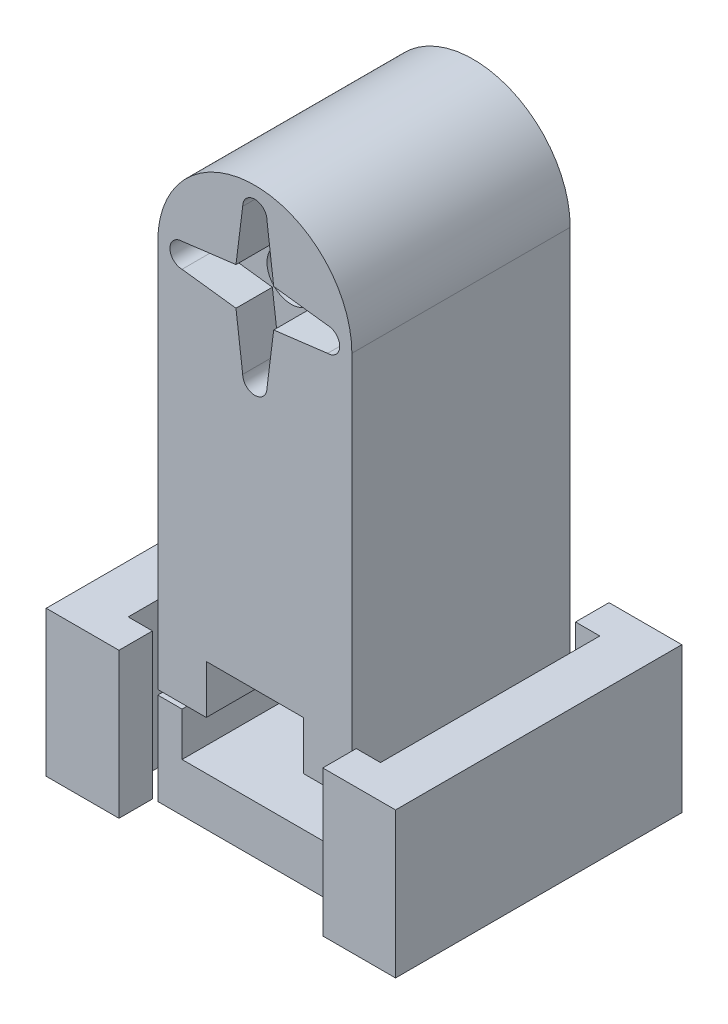
SolidWorks part; units mm, degrees
ref_plane "Alzado" through (0, 0, 0) normal (1, 0, 0) x (0, 1, 0)
ref_plane "Planta" through (0, 0, 0) normal (0, 0, 1) x (0, 1, 0)
ref_plane "Vista lateral" through (0, 0, 0) normal (0, 1, 0) x (-1, 0, 0)
sketch "Croquis1" plane through (0, 0, 0) normal (0, 0, 1) x (0, 1, 0)
  line L4 (0, 20) -> (40, 20)
  line L5 (0, -20) -> (40, -20)
  line L6 (0, 20) -> (-40, 20)
  line L7 (0, -20) -> (-40, -20)
  arc A0 (40, -20) -> (40, 20) centre (40, 0) ccw
  arc A1 (-40, 20) -> (-40, -20) centre (-40, 0) ccw
extrude "Saliente-Extruir1" add sketch "Croquis1" along normal blind 45
sketch "Croquis2" plane through (0, 0, 45) normal (0, 0, 1) x (1, 0, 0)
  line L8 (-15, 42.5) -> (-3.8891, 43.8891)
  line L9 (-3.8891, 43.8891) -> (-2.5, 55)
  line L10 (2.5, 55) -> (3.8891, 43.8891)
  line L11 (15, 42.5) -> (3.8891, 43.8891)
  line L12 (15, 37.5) -> (3.8891, 36.1109)
  line L13 (2.5, 25) -> (3.8891, 36.1109)
  line L14 (-2.5, 25) -> (-3.8891, 36.1109)
  line L15 (-15, 37.5) -> (-3.8891, 36.1109)
  arc A5 (-15, 42.5) -> (-15, 37.5) centre (-15, 40) ccw
  arc A6 (-2.5, 25) -> (2.5, 25) centre (0, 25) ccw
  arc A7 (15, 37.5) -> (15, 42.5) centre (15, 40) ccw
  arc A8 (2.5, 55) -> (-2.5, 55) centre (0, 55) ccw
extrude "Cortar-Extruir1" cut sketch "Croquis2" against normal blind 7.5
sketch "Croquis3" plane through (0, 0, 45) normal (0, 0, 1) x (1, 0, 0)
  circle A0 centre (0, 40) radius 5
extrude "Cortar-Extruir2" cut sketch "Croquis3" against normal blind 57.5
sketch "Croquis4" plane through (0, 0, 45) normal (0, 0, 1) x (1, 0, 0)
  line L1 (20, -40) -> (-21.8685, -40)
  line L2 (20, -40) -> (20, -61.001)
  line L3 (20, -61.001) -> (-21.8685, -61.001)
  line L4 (-21.8685, -40) -> (-21.8685, -61.001)
extrude "Cortar-Extruir3" cut sketch "Croquis4" against normal blind 57.5
sketch "Croquis5" plane through (0, 0, 45) normal (0, 0, 1) x (1, 0, 0)
  line L4 (0, -40) -> (10, -40)
  line L5 (20, -40) -> (-20, -40) construction
  line L6 (0, -40) -> (-10, -40)
  line L7 (-10, -40) -> (-10, 0)
  line L8 (-10, 0) -> (10, 0)
  line L9 (10, 0) -> (10, -40)
  dimension "D1" = 10
  dimension "D2" = 10
  dimension "D3" = 40
extrude "Cortar-Extruir4" cut sketch "Croquis5" against normal blind 40 from offset 2.5 offset against normal yes
sketch "Croquis6" plane through (0, 0, 45) normal (0, 0, 1) x (1, 0, 0)
  line L0 (0, -40) -> (-10, -40)
  line L1 (20, -40) -> (-20, -40) construction
  line L2 (-10, -40) -> (-10, -30)
  line L3 (-10, -30) -> (10, -30)
  line L4 (10, -30) -> (10, -40)
  line L5 (10, -40) -> (0, -40)
extrude "Cortar-Extruir5" cut sketch "Croquis6" against normal blind 45
sketch "Croquis7" plane through (0, 0, 45) normal (0, 0, 1) x (1, 0, 0)
  line L1 (-10, 0) -> (10, 0)
  line L2 (10, 0) -> (10, -10)
  line L3 (10, -10) -> (-10, -10)
  line L4 (-10, -10) -> (-10, 0)
extrude "Cortar-Extruir7" cut sketch "Croquis7" against normal blind 20 from offset 40 offset against normal yes
sketch "Croquis8" plane through (0, 0, 0) normal (0, 0, -1) x (1, 0, 0)
  line L1 (10, 30) -> (20, 30)
  line L2 (10, 30) -> (10, 60)
  line L3 (10, 60) -> (20, 60)
  line L4 (20, 30) -> (20, 60)
  line L5 (20, 60) -> (-20, 60)
  line L6 (20, 60) -> (20, 50)
  line L7 (20, 50) -> (-20, 50)
  line L8 (-20, 60) -> (-20, 50)
  line L9 (-10, 40) -> (-20, 40)
  line L10 (-10, 40) -> (-10, 60)
  line L11 (-10, 60) -> (-20, 60)
  line L12 (-20, 40) -> (-20, 60)
  line M20 (20, 40) -> (10, 40)
  dimension "D1" = 30
  dimension "D2" = 10
  dimension "D3" = 40
extrude "Saliente-Extruir2" add sketch "Croquis8" against normal blind 45 contours L7 L4 L3 L2 | L4 L7 L2 M20 | L10 L7 L2 L5
sketch "Croquis9" plane through (0, 0, 0) normal (0, 0, -1) x (-1, 0, 0)
  line L7 (-10, -40) -> (-15, -40)
  line L8 (-10, -40) -> (-10, -50)
  line L9 (-10, -50) -> (-15, -50)
  line L10 (-15, -40) -> (-15, -50)
  line L11 (10, -50) -> (15, -50)
  line L12 (10, -50) -> (10, -40)
  line L13 (10, -40) -> (15, -40)
  line L14 (15, -50) -> (15, -40)
extrude "Cortar-Extruir8" cut sketch "Croquis9" against normal blind 45
sketch "Croquis10" plane through (0, -60, 0) normal (0, -1, 0) x (1, 0, 0)
  circle A1 centre (0, 12.5) radius 3
extrude "Cortar-Extruir9" cut sketch "Croquis10" against normal blind 20
sketch "Croquis11" plane through (0, 0, 0) normal (0, 0, -1) x (1, 0, 0)
  line L0 (20, 60) -> (20, -40) construction
  line L1 (20, 40) -> (-20, 40)
  line L2 (20, 40) -> (20, 41)
  line L3 (20, 41) -> (-20, 41)
  line L4 (-20, 40) -> (-20, 41)
  line L5 (-20, -40) -> (-20, 60) construction
extrude "Cortar-Extruir12" cut sketch "Croquis11" against normal blind 45
sketch "Croquis12" plane through (0, 0, 45) normal (0, 0, 1) x (1, 0, 0)
  line L1 (-20, -60) -> (-15, -60)
  line L2 (-20, -60) -> (-20, -30)
  line L3 (-20, -30) -> (-15, -30)
  line L4 (-15, -60) -> (-15, -30)
  line L5 (20, -60) -> (15, -60)
  line L6 (20, -60) -> (20, -30)
  line L7 (20, -30) -> (15, -30)
  line L8 (15, -60) -> (15, -30)
  dimension "D1" = 30
  dimension "D2" = 30
extrude "Saliente-Extruir3" add sketch "Croquis12" along normal blind 7
sketch "Croquis13" plane through (20, 0, 0) normal (1, 0, 0) x (0, 1, 0)
  line L0 (-40, 0) -> (40, 0) construction
  line L1 (-60, 52) -> (-30, 52)
  line L2 (-60, 52) -> (-60, 0)
  line L3 (-60, 0) -> (-30, 0)
  line L4 (-30, 52) -> (-30, 0)
extrude "Saliente-Extruir4" add sketch "Croquis13" along normal blind 16
sketch "Croquis14" plane through (-20, 0, 0) normal (-1, 0, 0) x (0, -1, 0)
  line L1 (30, 52) -> (60, 52)
  line L2 (30, 52) -> (30, 0)
  line L3 (30, 0) -> (60, 0)
  line L4 (60, 52) -> (60, 0)
extrude "Saliente-Extruir5" add sketch "Croquis14" along normal blind 16
sketch "Croquis15" plane through (0, 0, 52) normal (0, 0, 1) x (1, 0, 0)
  line L0 (15, -60) -> (36, -60) construction
  line L1 (15, -30) -> (21, -30)
  line L2 (15, -30) -> (15, -60)
  line L3 (15, -60) -> (21, -60)
  line L4 (21, -30) -> (21, -60)
extrude "Cortar-Extruir13" cut sketch "Croquis15" against normal blind 7
sketch "Croquis16" plane through (0, 0, 52) normal (0, 0, 1) x (1, 0, 0)
  line L0 (-36, -60) -> (-15, -60) construction
  line L1 (-15, -30) -> (-21, -30)
  line L2 (-15, -30) -> (-15, -60)
  line L3 (-15, -60) -> (-21, -60)
  line L4 (-21, -30) -> (-21, -60)
extrude "Cortar-Extruir14" cut sketch "Croquis16" against normal blind 7
sketch "Croquis17" plane through (0, 0, 45) normal (0, 0, 1) x (1, 0, 0)
  line L0 (-21, -60) -> (21, -60) construction
  line L1 (20, -30) -> (21, -30)
  line L2 (20, -30) -> (20, -60)
  line L3 (20, -60) -> (21, -60)
  line L4 (21, -30) -> (21, -60)
  line L5 (-21, -30) -> (-20, -30)
  line L6 (-21, -30) -> (-21, -60)
  line L7 (-21, -60) -> (-20, -60)
  line L8 (-20, -30) -> (-20, -60)
extrude "Cortar-Extruir15" cut sketch "Croquis17" against normal blind 45
sketch "Croquis18" plane through (0, 0, 0) normal (0, 0, -1) x (-1, 0, 0)
  line L1 (36, -60) -> (21, -60)
  line L2 (36, -60) -> (36, -30)
  line L3 (36, -30) -> (21, -30)
  line L4 (21, -60) -> (21, -30)
  line L5 (-21, -60) -> (-36, -60)
  line L6 (-21, -60) -> (-21, -30)
  line L7 (-21, -30) -> (-36, -30)
  line L8 (-36, -60) -> (-36, -30)
extrude "Saliente-Extruir6" add sketch "Croquis18" along normal blind 7
sketch "Croquis19" plane through (0, 0, -7) normal (0, 0, -1) x (-1, 0, 0)
  line L0 (36, -30) -> (21, -30) construction
  line L1 (21, -60) -> (26, -60)
  line L2 (21, -60) -> (21, -30)
  line L3 (21, -30) -> (26, -30)
  line L4 (26, -60) -> (26, -30)
  point P17 (-26.757, -60)
  point P18 (-28.8529, -62.9007)
  dimension "D1" = 5
extrude "Cortar-Extruir16" cut sketch "Croquis19" against normal blind 45.2 from offset 6.9 offset against normal yes
sketch "Croquis20" plane through (0, 0, -7) normal (0, 0, -1) x (1, 0, 0)
  line L0 (21, 30) -> (36, 30) construction
  line L1 (21, 60) -> (26, 60)
  line L2 (21, 60) -> (21, 30)
  line L3 (21, 30) -> (26, 30)
  line L4 (26, 60) -> (26, 30)
extrude "Cortar-Extruir17" cut sketch "Croquis20" against normal blind 45.2 from offset 6.9
